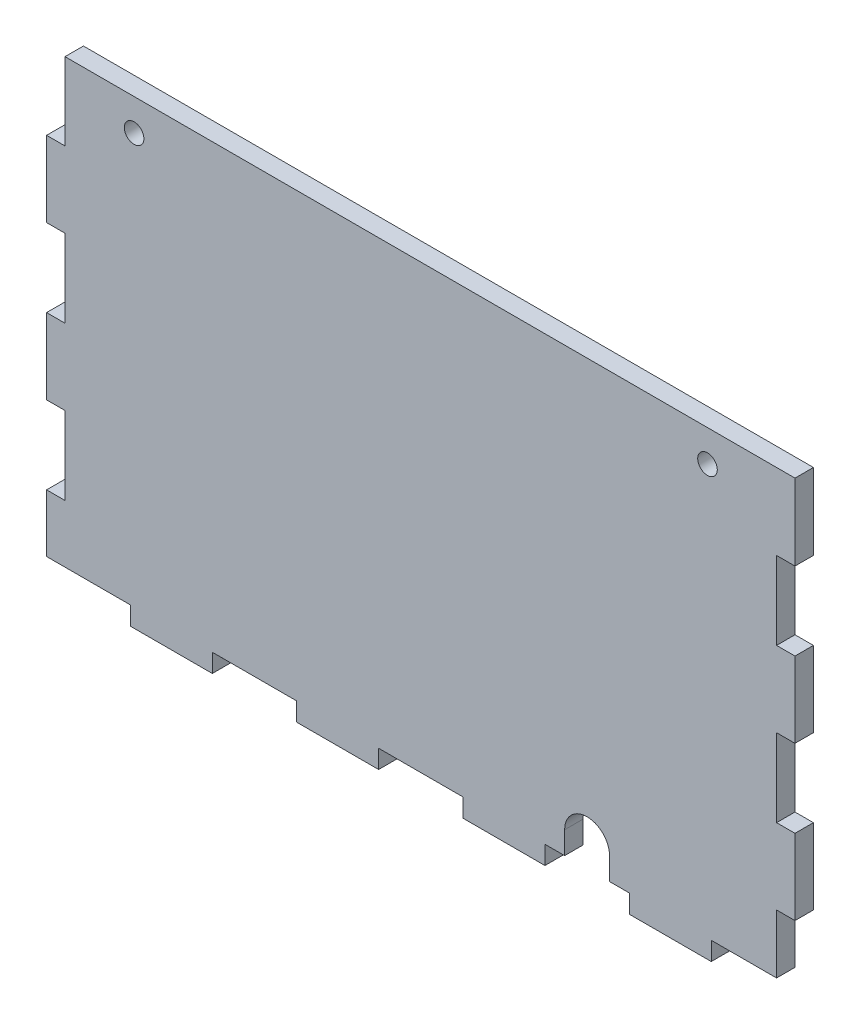
SolidWorks part; units mm, degrees
ref_plane "Front Plane" through (0, 0, 0) normal (0, 0, 1) x (1, 0, 0)
ref_plane "Top Plane" through (0, 0, 0) normal (0, 1, 0) x (1, 0, 0)
ref_plane "Right Plane" through (0, 0, 0) normal (1, 0, 0) x (0, 0, -1)
sketch "Sketch1" plane through (0, 0, 0) normal (0, 0, 1) x (1, 0, 0)
  line L1 (0, 0) -> (130, 0)
  line L2 (0, 0) -> (0, 80)
  line L3 (0, 80) -> (130, 80)
  line L4 (130, 0) -> (130, 80)
  dimension "D1" = 130
  dimension "D2" = 80
extrude "Boss-Extrude1" add sketch "Sketch1" along normal blind 3.2
sketch "Sketch2" plane through (0, 0, 3.2) normal (0, 0, 1) x (1, 0, 0)
  line L61 (14.4444, 3.2) -> (28.8889, 3.2) construction
  line L62 (0, 0) -> (14.4444, 0)
  line L67 (0, 0) -> (0, 3.2)
  line L72 (0, 3.2) -> (14.4444, 3.2)
  line L77 (14.4444, 0) -> (14.4444, 3.2)
  line L97 (28.8889, 0) -> (28.8889, 3.2)
  line L98 (28.8889, 0) -> (43.3333, 0)
  line L107 (43.3333, 0) -> (43.3333, 3.2)
  line L115 (28.8889, 3.2) -> (43.3333, 3.2)
  line L117 (43.3333, 3.2) -> (57.7778, 3.2) construction
  line L123 (57.7778, 0) -> (57.7778, 3.2)
  line L128 (57.7778, 0) -> (72.2222, 0)
  line L129 (72.2222, 0) -> (72.2222, 3.2)
  line L131 (57.7778, 3.2) -> (72.2222, 3.2)
  line L132 (72.2222, 3.2) -> (86.6667, 3.2) construction
  line L133 (86.6667, 0) -> (86.6667, 3.2)
  line L134 (86.6667, 0) -> (101.1111, 0)
  line L135 (101.1111, 0) -> (101.1111, 3.2)
  line L136 (86.6667, 3.2) -> (101.1111, 3.2)
  line L137 (101.1111, 3.2) -> (115.5556, 3.2) construction
  line L138 (115.5556, 0) -> (115.5556, 3.2)
  line L139 (115.5556, 0) -> (130, 0)
  line L142 (130, 0) -> (130, 80) construction
  line L143 (0, 80) -> (0, 0) construction
  line L144 (0, 13.3333) -> (3.2, 13.3333)
  line L145 (0, 13.3333) -> (0, 26.6667)
  line L146 (130, 3.2) -> (144.4444, 3.2) construction
  line L147 (0, 26.6667) -> (3.2, 26.6667)
  line L148 (3.2, 13.3333) -> (3.2, 26.6667)
  line L149 (3.2, 13.3333) -> (3.2, 0) construction
  line L150 (0, 40) -> (0, 53.3333)
  line L151 (0, 40) -> (3.2, 40)
  line L152 (3.2, 40) -> (3.2, 53.3333)
  line L153 (0, 53.3333) -> (3.2, 53.3333)
  line L154 (3.2, 40) -> (3.2, 26.6667) construction
  line L155 (0, 66.6667) -> (0, 80)
  line L156 (0, 66.6667) -> (3.2, 66.6667)
  line L157 (3.2, 66.6667) -> (3.2, 80)
  line L158 (0, 80) -> (3.2, 80)
  line L159 (3.2, 66.6667) -> (3.2, 53.3333) construction
  line L160 (130, 80) -> (0, 80) construction
  line L161 (126.8, 80) -> (126.8, 66.6667) construction
  line L162 (126.8, 40) -> (126.8, 26.6667)
  line L163 (126.8, 66.6667) -> (130, 66.6667)
  line L164 (126.8, 66.6667) -> (126.8, 53.3333)
  line L165 (126.8, 53.3333) -> (130, 53.3333)
  line L166 (130, 66.6667) -> (130, 53.3333)
  line L167 (126.8, 40) -> (130, 40)
  line L168 (130, 40) -> (130, 26.6667)
  line L169 (126.8, 26.6667) -> (130, 26.6667)
  line L170 (126.8, 53.3333) -> (126.8, 40) construction
  line L172 (126.8, 13.3333) -> (130, 13.3333)
  line L173 (130, 13.3333) -> (130, 0)
  line L175 (126.8, 26.6667) -> (126.8, 13.3333) construction
  line L183 (115.5556, 3.2) -> (130, 3.2) [skipped]
  line L184 (130, 0) -> (130, 3.2) [skipped]
  line L185 (126.8, 13.3333) -> (126.8, 3.2)
  line L186 (126.8, 3.2) -> (115.5556, 3.2)
  line L187 (126.8, 0) -> (130, 0) [skipped]
  line L188 (126.8, 13.3333) -> (126.8, 0) [skipped]
  dimension "D2" = 3.2
  dimension "D4" = 3.2
  dimension "D6" = 3.2
  dimension "D1" = 5
  dimension "D3" = 3
  dimension "D5" = 3
extrude "Cut-Extrude1" cut sketch "Sketch2" against normal through all
other "Move Face1" face at (128.4, 53.3333, 1.6) face at (128.4, 26.6667, 1.6) face at (128.4, 13.3333, 1.6) face at (128.4, 40, 1.6) face at (128.4, 66.6667, 1.6) face at (115.5556, 1.6, 1.6) face at (86.6667, 1.6, 1.6) face at (57.7778, 1.6, 1.6) face at (28.8889, 1.6, 1.6) face at (14.4444, 1.6, 1.6) face at (43.3333, 1.6, 1.6) face at (72.2222, 1.6, 1.6) face at (101.1111, 1.6, 1.6) face at (1.6, 26.6667, 1.6) face at (1.6, 13.3333, 1.6) face at (1.6, 40, 1.6) face at (1.6, 53.3333, 1.6) face at (1.6, 66.6667, 1.6) parameters "D1"=0.1
sketch "Sketch3" plane through (0, 0, 3.2) normal (0, 0, 1) x (1, 0, 0)
  line L0 (0, 66.5667) -> (0, 53.4333) construction
  line L1 (130, 80) -> (3.2, 80) construction
  line L2 (0, 66.5667) -> (130, 66.7667) construction
  line L3 (65, 66.6667) -> (65, 50066.6667) construction
  circle A0 centre (15.2, 74.5) radius 1.7
  circle A1 centre (114.8, 74.5) radius 1.7
  point P10 (65, 66.6667)
  dimension "D1" = 3.4
  dimension "D2" = 15.2
  dimension "D3" = 5.5
extrude "Cut-Extrude2" cut sketch "Sketch3" against normal up to next
sketch "Sketch4" plane through (0, 0, 0) normal (0, 0, -1) x (-1, 0, 0)
  line L0 (-97.7889, 3.2) -> (-97.7889, 7.1)
  line L1 (-101.2111, 3.2) -> (-86.5667, 3.2) construction
  line L2 (-89.9889, 3.2) -> (-89.9889, 7.1)
  line L3 (-97.7889, 3.2) -> (-89.9889, 3.2)
  line L4 (-101.2111, 0) -> (-86.5667, 0) construction
  line L5 (-101.2111, 0) -> (-115.4556, 0) construction
  line L6 (-101.2111, 0) -> (-101.2111, 3.2) construction
  line L7 (-72.3222, 0) -> (-86.5667, 0) construction
  arc A0 (-97.7889, 7.1) -> (-89.9889, 7.1) centre (-93.8889, 7.1) cw
  point P15 (-93.8889, 0)
  point P16 (0, 0)
  point P17 (0, 0)
  dimension "D2" = 7.8
  dimension "D1" = 7.8
extrude "Cut-Extrude3" cut sketch "Sketch4" against normal up to next
equation "\"wall_thickness\"= 3.2mm"
equation "\"D1@Boss-Extrude1\"=\"wall_thickness\""
equation "\"slot_width_tolerance\"= 0.1mm"
equation "\"slot_depth\"= 3.2mm"
equation "\"D2@Sketch2\"=\"slot_depth\""
equation "\"D4@Sketch2\"=\"slot_depth\""
equation "\"D6@Sketch2\"=\"slot_depth\""
equation "\"D2@Sketch3\"=12.00mm+\"slot_depth\""
